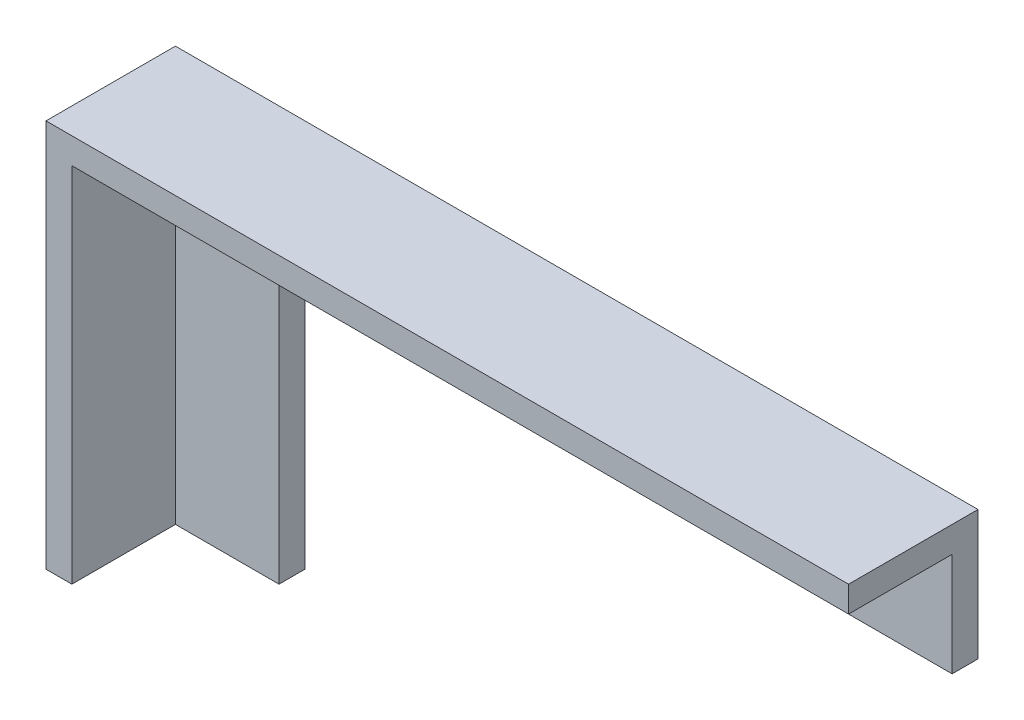
SolidWorks part; units mm, degrees
ref_plane "Plan de face" through (0, 0, 0) normal (0, 0, 1) x (1, 0, 0)
ref_plane "Plan de dessus" through (0, 0, 0) normal (0, 1, 0) x (1, 0, 0)
ref_plane "Plan de droite" through (0, 0, 0) normal (1, 0, 0) x (0, 0, -1)
sketch "Esquisse1" plane through (0, 0, 0) normal (0, 0, 1) x (1, 0, 0)
  line L0 (0, 0) -> (31, 0)
  line L1 (31, 0) -> (31, -5)
  line L2 (31, -5) -> (5, -5)
  line L3 (5, -5) -> (5, -15)
  line L4 (5, -15) -> (0, -15)
  line L5 (0, -15) -> (0, 0)
  dimension "D1" = 31
  dimension "D2" = 15
  dimension "D3" = 5
  dimension "D4" = 5
extrude "Boss.-Extru.1" add sketch "Esquisse1" along normal blind 5
sketch "Esquisse2" plane through (0, 0, 5) normal (0, 0, 1) x (1, 0, 0)
  line L0 (5, -15) -> (5, -5)
  line L1 (5, -5) -> (31, -5)
  line L2 (31, -5) -> (31, 0)
  line L5 (1, -1) -> (1, -15)
  line L7 (1, -15) -> (5, -15)
  line L8 (0, 0) -> (0, -15) construction
  line L9 (1, -1) -> (31, -1)
  point P10 (30.5276, -0.8814)
  line M9 (0, -15) -> (5, -15)
  line M10 (5, -15) -> (5, -5)
  line M11 (5, -5) -> (31, -5)
  line M12 (31, -5) -> (31, 0)
  dimension "D1" = 1
  dimension "D2" = 1
extrude "Enlèv. mat.-Extru.1" cut sketch "Esquisse2" against normal blind 4 contours L9 L5 M9 M10 M11 M12
